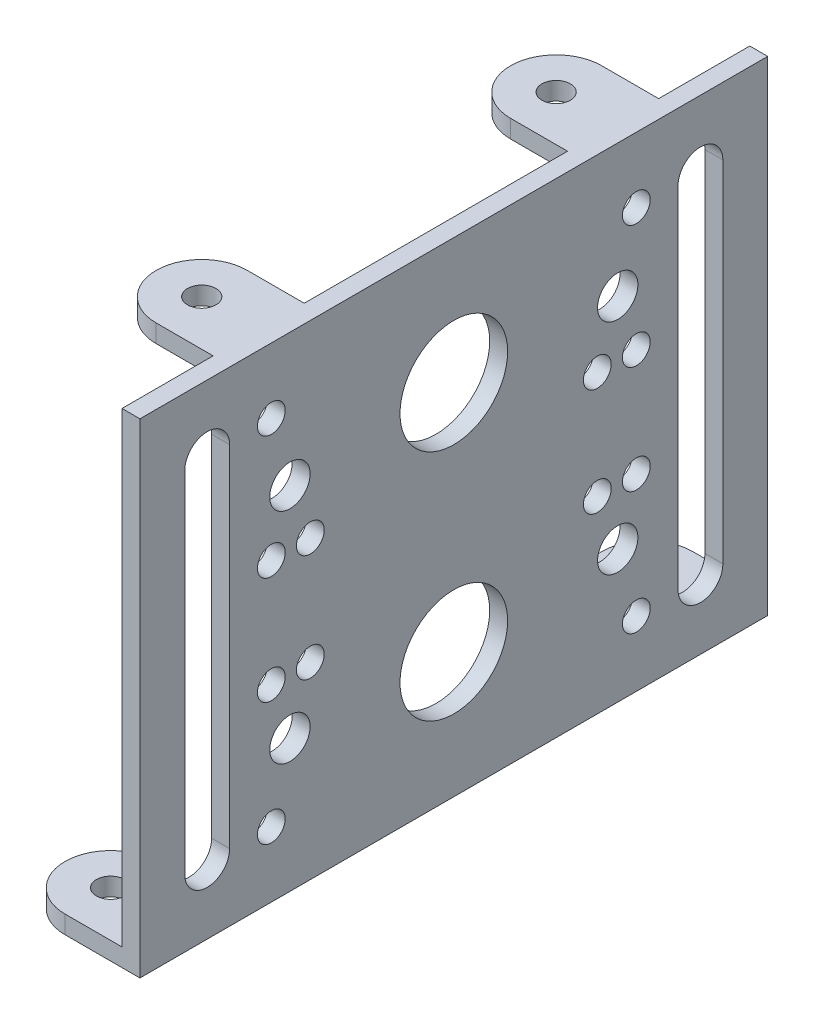
SolidWorks part; units mm, degrees
ref_plane "Front Plane" through (0, 0, 0) normal (0, 0, 1) x (1, 0, 0)
ref_plane "Top Plane" through (0, 0, 0) normal (0, 1, 0) x (1, 0, 0)
ref_plane "Right Plane" through (0, 0, 0) normal (1, 0, 0) x (0, 0, -1)
sketch "Sketch1" plane through (0, 0, 0) normal (1, 0, 0) x (0, 0, -1)
  line L0 (-18, 0) -> (18, 0)
  line L1 (0, 18) -> (0, -18)
  line L2 (88.0775, -1.458) -> (88.0775, 52.542)
  line L3 (53.0775, 52.542) -> (123.0775, 52.542)
  line L4 (53.0775, 52.542) -> (53.0775, -1.458)
  line L5 (53.0775, -1.458) -> (123.0775, -1.458)
  line L6 (123.0775, 52.542) -> (123.0775, -1.458)
  line L7 (60.5775, 47.542) -> (60.5775, 52.542)
  line L8 (58.0775, 25.542) -> (63.0775, 25.542)
  line L9 (58.0775, 6.042) -> (58.0775, 45.042)
  line L10 (113.0775, 6.042) -> (113.0775, 45.042)
  line L11 (63.0775, 6.042) -> (63.0775, 45.042)
  line L12 (118.0775, 6.042) -> (118.0775, 45.042)
  line L13 (53.0775, 25.542) -> (123.0775, 25.542)
  line L14 (118.0775, 25.542) -> (113.0775, 25.542)
  circle A0 centre (0, 0) radius 18
  circle A1 centre (7, 0) radius 6
  circle A2 centre (0, 16) radius 1.5
  circle A3 centre (0, -16) radius 1.5
  circle A4 centre (0, 0) radius 16
  circle A5 centre (13.5603, -8.4922) radius 1.5
  circle A6 centre (-13.5603, -8.4922) radius 1.5
  circle A7 centre (13.5603, 8.4922) radius 1.5
  circle A8 centre (-13.5603, 8.4922) radius 1.5
  circle A9 centre (69.8025, 13.3358) radius 2.25
  arc A10 (63.0775, 45.042) -> (58.0775, 45.042) centre (60.5775, 45.042) ccw
  circle A11 centre (106.3525, 13.3358) radius 2.25
  arc A12 (63.0775, 6.042) -> (58.0775, 6.042) centre (60.5775, 6.042) cw
  circle A13 centre (104.0775, 31.542) radius 1.5
  circle A14 centre (72.0775, 31.542) radius 1.5
  circle A15 centre (88.0775, 38.542) radius 6
  arc A16 (113.0775, 6.042) -> (118.0775, 6.042) centre (115.5775, 6.042) ccw
  circle A17 centre (106.3525, 37.7483) radius 2.25
  circle A18 centre (88.0775, 12.542) radius 6
  arc A19 (113.0775, 45.042) -> (118.0775, 45.042) centre (115.5775, 45.042) cw
  circle A20 centre (69.8025, 37.7483) radius 2.25
  circle A21 centre (72.0775, 19.542) radius 1.5
  circle A22 centre (104.0775, 19.542) radius 1.5
  dimension "D1" = 36
  dimension "D2" = 12
  dimension "D4" = 3
  dimension "D6" = 3
  dimension "D11" = 5
  dimension "D13" = 5
  dimension "D17" = 3
  dimension "D14" = 5
  dimension "D3" = 11
  dimension "D5" = 2
  dimension "D7" = 15.5
  dimension "D8" = 10.731
  dimension "D9" = 54
  dimension "D10" = 70
  dimension "D12" = 14
extrude "Boss-Extrude1" add sketch "Sketch1" along normal blind 2 contours A15 L2 L3 L7 A10 L11 L13 A14 A20 | L2 A18 L13 L11 A12 L9 L4 L5 A21 A9 | A10 L7 L3 L4 L13 L9 | L2 A18 L5 L6 L13 L12 A16 L10 A22 A11 | L10 A19 L12 L13 L6 L3 L2 A15 A17 A13
sketch "Sketch2" plane through (0, -1.458, 0) normal (0, -1, 0) x (1, 0, 0)
  line L0 (0, -88.0775) -> (2, -88.0775)
  line L1 (0, -53.0775) -> (2, -53.0775)
  line L2 (0, -53.0775) -> (0, -123.0775)
  line L3 (0, -123.0775) -> (2, -123.0775)
  line L4 (2, -53.0775) -> (2, -123.0775)
  line L5 (0, -53.0775) -> (-2.5, -53.0775)
  line L6 (0, -53.0775) -> (0, -58.0775)
  line L7 (0, -58.0775) -> (-2.5, -58.0775)
  line L8 (0, -58.0775) -> (0, -63.0775)
  line L9 (-2.5, -53.0775) -> (-2.5, -58.0775)
  line L10 (-5, -55.5775) -> (0, -55.5775)
  line L11 (0, -63.0775) -> (-2.5, -63.0775)
  line L12 (0, -63.0775) -> (0, -68.0775)
  line L13 (0, -68.0775) -> (-2.5, -68.0775)
  line L14 (-2.5, -63.0775) -> (-2.5, -68.0775)
  line L15 (-5, -65.5775) -> (0, -65.5775)
  line L16 (-5, -110.5775) -> (0, -110.5775)
  line L17 (-2.5, -113.0775) -> (-2.5, -108.0775)
  line L18 (0, -108.0775) -> (-2.5, -108.0775)
  line L19 (0, -113.0775) -> (0, -108.0775)
  line L20 (0, -113.0775) -> (-2.5, -113.0775)
  line L21 (-5, -120.5775) -> (0, -120.5775)
  line L22 (-2.5, -123.0775) -> (-2.5, -118.0775)
  line L23 (0, -118.0775) -> (0, -113.0775)
  line L24 (0, -118.0775) -> (-2.5, -118.0775)
  line L25 (0, -123.0775) -> (0, -118.0775)
  line L26 (0, -123.0775) -> (-2.5, -123.0775)
  line L28 (0, -53.0775) -> (2, -53.0775)
  line L29 (0, -53.0775) -> (0, -123.0775)
  line L30 (0, -123.0775) -> (2, -123.0775)
  line L31 (2, -53.0775) -> (2, -123.0775)
  circle A0 centre (-2.5, -55.5775) radius 1.5875
  arc A1 (-2.5, -53.0775) -> (-2.5, -58.0775) centre (-2.5, -55.5775) ccw
  circle A2 centre (-2.5, -65.5775) radius 1.5875
  arc A3 (-2.5, -63.0775) -> (-2.5, -68.0775) centre (-2.5, -65.5775) ccw
  arc A4 (-2.5, -113.0775) -> (-2.5, -108.0775) centre (-2.5, -110.5775) cw
  circle A5 centre (-2.5, -110.5775) radius 1.5875
  arc A6 (-2.5, -123.0775) -> (-2.5, -118.0775) centre (-2.5, -120.5775) cw
  circle A7 centre (-2.5, -120.5775) radius 1.5875
  line M1 (0, -53.0775) -> (0, -123.0775)
  dimension "D1" = 3.175
  dimension "D2" = 35
  dimension "D3" = 5
extrude "Boss-Extrude3" add sketch "Sketch2" against normal blind 2 contours L21 A7 L22 L26 L2 | L22 A7 L21 A6 | L21 A7 L22 A6 | L22 A7 L21 L2 L24 | L16 A5 L17 L20 L2 | L17 A5 L16 A4 | L16 A5 L17 A4 | L17 A5 L16 L2 L18 | A2 L14 L13 L12 L15 | A2 L15 L11 L14 M1 | L14 A3 L15 A2 | L15 A3 L14 A2 | L10 A1 L9 A0 | A0 L9 L7 L6 L10 | A0 L10 L5 L9 M1 | L9 A1 L10 A0
sketch "Sketch3" plane through (0, 0.542, 0) normal (0, 1, 0) x (1, 0, 0)
  line L1 (0, 113.0775) -> (-7.5213, 113.0775)
  line L2 (0, 113.0775) -> (0, 62.0203)
  line L3 (0, 62.0203) -> (-7.5213, 62.0203)
  line L4 (-7.5213, 113.0775) -> (-7.5213, 62.0203)
extrude "Cut-Extrude1" cut sketch "Sketch3" against normal blind 10
sketch "Sketch4" plane through (0, 52.542, 0) normal (0, 1, 0) x (1, 0, 0)
  line L0 (0, 123.0775) -> (0, 113.0775)
  line L1 (0, 53.0775) -> (0, 123.0775) construction
  line L2 (2, 88.0775) -> (0, 88.0775)
  line L3 (2, 53.0775) -> (2, 123.0775) construction
  line L4 (0, 68.0775) -> (-2.5, 68.0775)
  line L5 (0, 113.0775) -> (-2.5, 113.0775)
  line L6 (0, 113.0775) -> (0, 108.0775)
  line L7 (0, 108.0775) -> (-2.5, 108.0775)
  line L8 (0, 63.0775) -> (0, 68.0775)
  line L9 (0, 63.0775) -> (-2.5, 63.0775)
  arc A0 (-2.5, 113.0775) -> (-2.5, 108.0775) centre (-2.5, 110.5775) ccw
  circle A1 centre (-2.5, 110.5775) radius 1.5875
  circle A2 centre (-2.5, 65.5775) radius 1.5875
  arc A3 (-2.5, 63.0775) -> (-2.5, 68.0775) centre (-2.5, 65.5775) cw
  line M1 (0, 123.0775) -> (0, 53.0775)
  dimension "D1" = 3.175
extrude "Boss-Extrude4" add sketch "Sketch4" against normal blind 2 contours L5 A0 L7 A1 M1 | A3 L9 L4 A2 M1
sketch "Sketch5" plane through (2, 0, 0) normal (1, 0, 0) x (0, 0, -1)
  line L0 (110.9275, 22.082) -> (108.4275, 22.082)
  line L1 (65.2275, 22.082) -> (110.9275, 22.082)
  line L2 (65.2275, 22.082) -> (65.2275, 3.282)
  line L3 (65.2275, 3.282) -> (110.9275, 3.282)
  line L4 (110.9275, 22.082) -> (110.9275, 3.282)
  line L5 (108.4275, 22.082) -> (108.4275, 19.542)
  line L6 (88.0775, 22.082) -> (88.0775, 18.231)
  line L7 (72.0775, 19.542) -> (67.7275, 19.542)
  line L8 (69.9025, 19.542) -> (69.9025, 20.0633)
  line L9 (53.0775, 25.542) -> (60.1702, 25.542)
  line L10 (53.0775, 52.542) -> (53.0775, -1.458) construction
  line L11 (69.9025, 31.542) -> (69.9025, 31.0207)
  line L12 (72.0775, 31.542) -> (67.7275, 31.542)
  line L13 (88.0775, 29.002) -> (88.0775, 32.853)
  line L14 (108.4275, 29.002) -> (108.4275, 31.542)
  line L15 (110.9275, 29.002) -> (110.9275, 47.802)
  line L16 (65.2275, 47.802) -> (110.9275, 47.802)
  line L17 (65.2275, 29.002) -> (65.2275, 47.802)
  line L18 (65.2275, 29.002) -> (110.9275, 29.002)
  line L19 (110.9275, 29.002) -> (108.4275, 29.002)
  circle A0 centre (108.4275, 19.542) radius 1.55
  circle A1 centre (67.7275, 19.542) radius 1.55
  circle A2 centre (67.7275, 5.822) radius 1.55
  circle A3 centre (108.4275, 5.822) radius 1.55
  circle A4 centre (72.0775, 19.542) radius 1.55
  circle A5 centre (104.0775, 19.542) radius 1.55
  circle A6 centre (104.0775, 31.542) radius 1.55
  circle A7 centre (72.0775, 31.542) radius 1.55
  circle A8 centre (108.4275, 45.262) radius 1.55
  circle A9 centre (67.7275, 45.262) radius 1.55
  circle A10 centre (67.7275, 31.542) radius 1.55
  circle A11 centre (108.4275, 31.542) radius 1.55
  dimension "D4" = 3.1
  dimension "D1" = 45.7
  dimension "D2" = 18.8
  dimension "D3" = 2.5
extrude "Cut-Extrude2" cut sketch "Sketch5" against normal blind 2
sketch "Sketch7" plane through (0, 0.542, 0) normal (0, 1, 0) x (1, 0, 0)
  line L0 (0, 53.0775) -> (0, 63.2375)
  line L1 (0, 53.0775) -> (-2.5, 53.0775) construction
  line L2 (0, 53.0775) -> (0, 63.0775) construction
  line L3 (0, 58.1575) -> (-6.35, 58.1575)
  line L4 (0, 63.2375) -> (-6.35, 63.2375)
  line L5 (0, 53.0775) -> (-6.35, 53.0775)
  line L6 (0, 88.0775) -> (-33.5825, 88.0775)
  line L7 (0, 68.0775) -> (0, 108.0775) construction
  line L8 (0, 123.0775) -> (-6.35, 123.0775)
  line L9 (0, 112.9175) -> (-6.35, 112.9175)
  line L10 (0, 117.9975) -> (-6.35, 117.9975)
  line L11 (0, 123.0775) -> (0, 112.9175)
  arc A0 (-6.35, 63.2375) -> (-6.35, 53.0775) centre (-6.35, 58.1575) ccw
  circle A1 centre (-6.35, 58.1575) radius 1.5875
  circle A2 centre (-6.35, 117.9975) radius 1.5875
  arc A3 (-6.35, 112.9175) -> (-6.35, 123.0775) centre (-6.35, 117.9975) cw
  dimension "D2" = 3.175
  dimension "D1" = 10.16
extrude "Boss-Extrude6" add sketch "Sketch7" against normal blind 2
sketch "Sketch8" plane through (0, 52.542, 0) normal (0, 1, 0) x (1, 0, 0)
  line L1 (0, 113.0775) -> (-8.5563, 113.0775)
  line L2 (0, 113.0775) -> (0, 61.2213)
  line L3 (0, 61.2213) -> (-8.5563, 61.2213)
  line L4 (-8.5563, 113.0775) -> (-8.5563, 61.2213)
extrude "Cut-Extrude3" cut sketch "Sketch8" against normal blind 2
sketch "Sketch9" plane through (0, 52.542, 0) normal (0, 1, 0) x (1, 0, 0)
  line L0 (0, 123.0775) -> (0, 112.9175)
  line L1 (0, 112.9175) -> (0, 102.7575)
  line L2 (0, 53.0775) -> (0, 123.0775) construction
  line L3 (0, 88.0775) -> (2, 88.0775)
  line L4 (2, 53.0775) -> (2, 123.0775) construction
  line L5 (0, 107.8375) -> (-6.35, 107.8375)
  line L6 (-10.16, 64.9574) -> (-10.16, 71.6776)
  line L7 (0, 112.9175) -> (-6.35, 112.9175)
  line L8 (0, 112.9175) -> (0, 102.7575)
  line L9 (0, 102.7575) -> (-6.35, 102.7575)
  line L10 (-10.16, 111.1976) -> (-10.16, 104.4774)
  line L11 (0, 73.3975) -> (-6.35, 73.3975)
  line L12 (0, 63.2375) -> (0, 73.3975)
  line L13 (0, 63.2375) -> (-6.35, 63.2375)
  line L14 (0, 68.3175) -> (-6.35, 68.3175)
  line L15 (0, 63.2375) -> (0, 73.3975)
  arc A0 (-6.35, 112.9175) -> (-6.35, 102.7575) centre (-6.35, 107.8375) ccw
  circle A1 centre (-6.35, 107.8375) radius 1.5875
  circle A2 centre (-6.35, 68.3175) radius 1.5875
  arc A3 (-6.35, 63.2375) -> (-6.35, 73.3975) centre (-6.35, 68.3175) cw
  dimension "D3" = 3.175
  dimension "D1" = 10.16
  dimension "D2" = 6.35
extrude "Boss-Extrude31" add sketch "Sketch9" against normal blind 2
